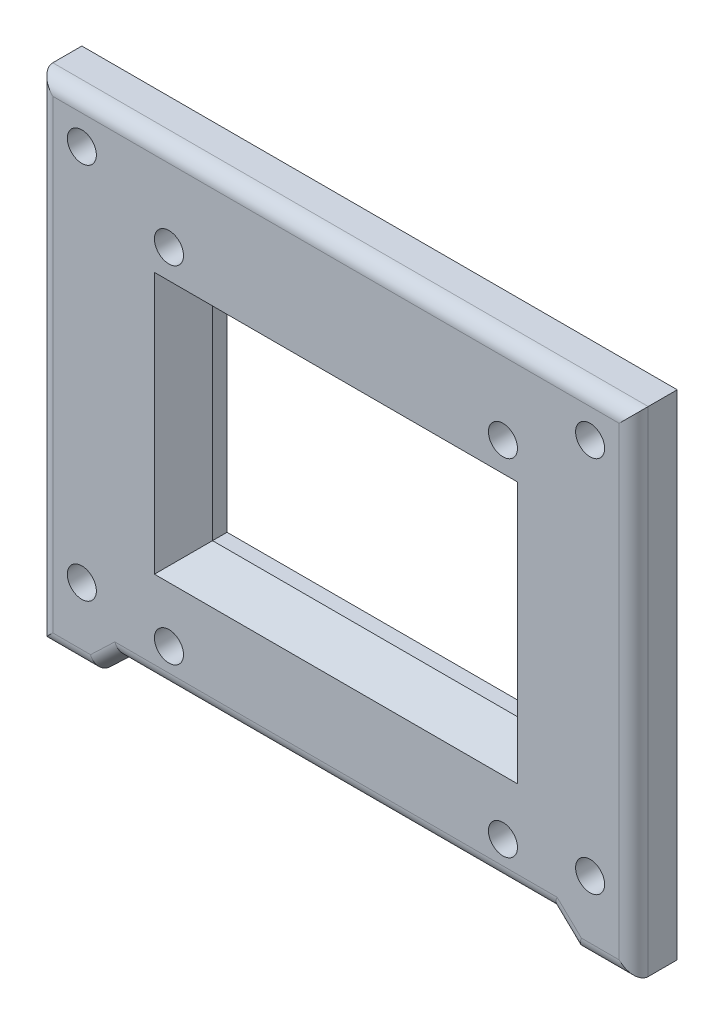
SolidWorks part; units mm, degrees
ref_plane "前视基准面" through (0, 0, 0) normal (0, 0, 1) x (1, 0, 0)
ref_plane "上视基准面" through (0, 0, 0) normal (0, 1, 0) x (1, 0, 0)
ref_plane "右视基准面" through (0, 0, 0) normal (1, 0, 0) x (0, 0, -1)
sketch "草图1" plane through (0, 0, 0) normal (0, 0, 1) x (1, 0, 0)
  line L1 (-11.4284, 14.907) -> (9.5716, 14.907)
  line L2 (-11.4284, 14.907) -> (-11.4284, 0.907)
  line L3 (-11.4284, 0.907) -> (9.5716, 0.907)
  line L4 (9.5716, 14.907) -> (9.5716, 0.907)
  line L5 (-21.4284, 24.907) -> (19.5716, 24.907)
  line L6 (-21.4284, 24.907) -> (-21.4284, -9.093)
  line L7 (-21.4284, -9.093) -> (-17.4284, -9.093)
  line L8 (19.5716, 24.907) -> (19.5716, -9.093)
  line L11 (17.6968, -9.093) -> (19.5716, -9.093)
  line L18 (-0.9284, 24.907) -> (-0.9284, 31.2215) construction
  line L19 (-17.4284, -9.093) -> (-15.7564, -7.493)
  line L20 (-0.9284, 31.2215) -> (-0.9284, -25.8497) construction
  line L21 (-15.7564, -7.493) -> (13.8997, -7.493)
  line L23 (15.5716, -9.093) -> (13.8997, -7.493)
  line L24 (15.5716, -9.093) -> (17.6968, -9.093)
  circle A0 centre (-12.4284, 18.907) radius 1
  circle A1 centre (-12.4284, -4.893) radius 1
  circle A2 centre (10.5716, 18.907) radius 1
  circle A3 centre (10.5716, -4.893) radius 1
  point P15 (-0.8749, -7.493)
  point P17 (-0.9284, -7.493)
  dimension "D2" = 2
  dimension "D3" = 2
  dimension "D4" = 2
  dimension "D7" = 2
  dimension "D8" = 23.8
  dimension "D9" = 23.8
  dimension "D1" = 14
  dimension "D5" = 10
  dimension "D6" = 10
  dimension "D10" = 0
  dimension "D11" = 0
  dimension "D12" = 4
  dimension "D13" = 4
  dimension "D14" = 1
  dimension "D15" = 1
  dimension "D16" = 21
  dimension "D17" = 10
  dimension "D18" = 10
  dimension "D19" = 34
  dimension "D20" = 41
  dimension "D21" = 4
  dimension "D22" = 1.6
extrude "凸台-拉伸1" add sketch "草图1" along normal blind 3
chamfer "倒角1" distance 2 angle 45 4 edges at (-11.4284, 7.907, 3) (-0.9284, 14.907, 3) (9.5716, 7.907, 3) (-0.9284, 0.907, 3)
fillet "圆角2" radius 1 8 edges at (14.7357, -8.293, 3) (-16.5924, -8.293, 3) (-19.4284, -9.093, 3) (-0.9284, -7.493, 3) (17.5716, -9.093, 3) (19.5716, 7.907, 3) (-0.9284, 24.907, 3) (-21.4284, 7.907, 3)
sketch "草图11" plane through (0, 0, 3) normal (0, 0, 1) x (1, 0, 0)
  line L0 (18.5716, 23.907) -> (-20.4284, 23.907) construction
  line L1 (-20.4284, 23.907) -> (-20.4284, -8.093) construction
  line L2 (18.5716, -8.093) -> (18.5716, 23.907) construction
  line L3 (-20.4284, -8.093) -> (-17.8297, -8.093) construction
  line L4 (15.973, -8.093) -> (18.5716, -8.093) construction
  circle A0 centre (-18.4284, 21.907) radius 1
  circle A1 centre (-18.4284, -4.093) radius 1
  circle A2 centre (16.5716, 21.907) radius 1
  circle A3 centre (16.5716, -4.093) radius 1
  dimension "D1" = 2
  dimension "D2" = 2
  dimension "D3" = 2
  dimension "D4" = 2
  dimension "D5" = 2
  dimension "D8" = 2
  dimension "D9" = 2
  dimension "D10" = 2
  dimension "D11" = 4
  dimension "D12" = 4
  dimension "D6" = 2
  dimension "D7" = 2
extrude "切除-拉伸1" cut sketch "草图11" against normal through all
